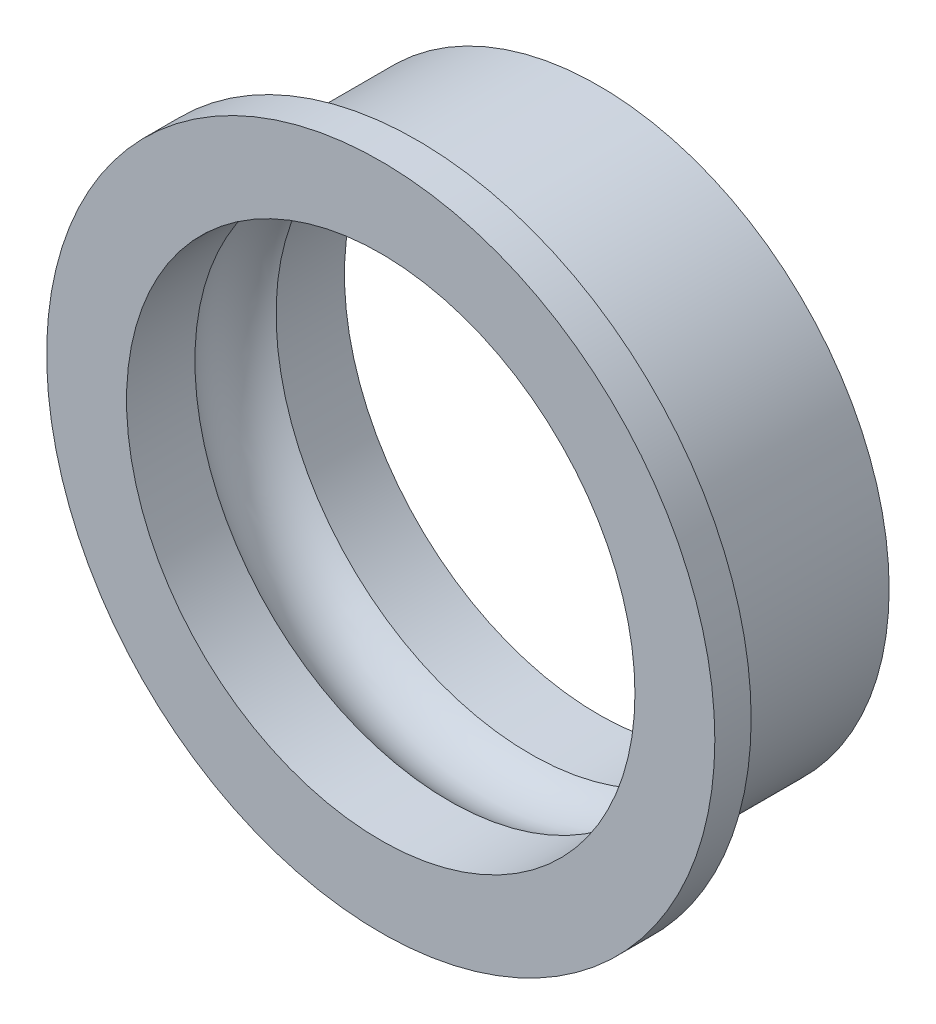
SolidWorks part; units mm, degrees
material "AISI 4340 Acier normalisé"
ref_plane "Face" through (0, 0, 0) normal (0, 0, 1) x (1, 0, 0)
ref_plane "Dessus" through (0, 0, 0) normal (0, 1, 0) x (1, 0, 0)
ref_plane "Droite" through (0, 0, 0) normal (1, 0, 0) x (0, 0, -1)
sketch "Esquisse1" plane through (0, 0, 0) normal (0, 0, 1) x (1, 0, 0)
  circle A0 centre (0, 0) radius 3.5
  circle A1 centre (0, 0) radius 4
  dimension "D1" = 7
  dimension "D2" = 8
extrude "Boss.-Extru.1" add sketch "Esquisse1" along normal mid plane 3
sketch "Esquisse2" plane through (0, 0, 1.5) normal (0, 0, 1) x (1, 0, 0)
  circle A0 centre (0, 0) radius 4.6
  circle A1 centre (0, 0) radius 4
  circle A2 centre (0, 0) radius 4
  dimension "D2" = 9.2
  dimension "D1" = 0
extrude "Boss.-Extru.2" add sketch "Esquisse2" against normal blind 0.5
sketch "Esquisse3" plane through (0, 0, 0) normal (0, 1, 0) x (1, 0, 0)
  line L0 (-3.5, -1.5) -> (-3.5, 1.5) construction
  line L4 (-3.5, -0.559) -> (-3.5, 0.559)
  line L5 (-3.5, 0) -> (-1.8361, 0) construction
  line L6 (-3.5, 1.5) -> (-3.5, -1.5) construction
  arc A0 (-3.5, 0.559) -> (-3.5, -0.559) centre (-3, 0) ccw
  dimension "D2" = 0.75
  dimension "D1" = 0.5
revolve "Enlèvement de matière-Révolution1" cut sketch "Esquisse3" angle 360 about axis through (0, 0, 1.5) along (0, 0, -1)
